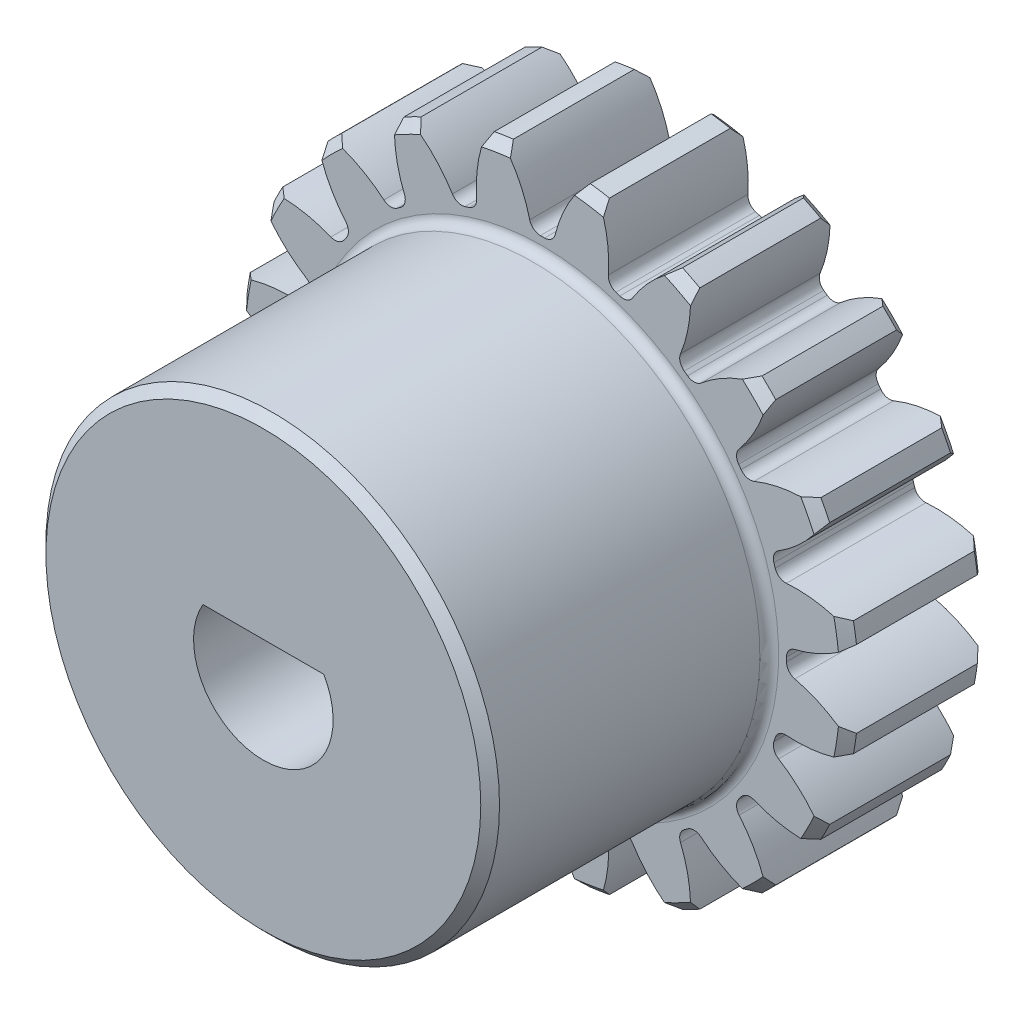
SolidWorks part; units mm, degrees
ref_plane "Front Plane" through (0, 0, 0) normal (0, 0, 1) x (1, 0, 0)
ref_plane "Top Plane" through (0, 0, 0) normal (0, 1, 0) x (1, 0, 0)
ref_plane "Right Plane" through (0, 0, 0) normal (1, 0, 0) x (0, 0, -1)
sketch "Sketch1" plane through (0, 0, 0) normal (0, 0, 1) x (1, 0, 0)
  line L0 (0, 0) -> (0, 8) construction
  line L1 (-2.5712, 8.9358) -> (2.5712, 7.0642) construction
  circle A0 centre (0, 0) radius 7 construction
  circle A1 centre (0, 0) radius 8.8 construction
  circle A2 centre (0, 0) radius 8 construction
  circle A3 centre (0, 0) radius 7.5175 construction
  circle A4 centre (0, 0) radius 6.5 construction
  circle A5 centre (0, 0) radius 2.5 construction
  point P8 (0.4, 0)
  point P13 (10, 0)
  dimension "OD" = 17.6
  dimension "Root Diameter" = 14
  dimension "Gear Pitch Diameter" = 16
  dimension "Base Diameter" = 15.0351
  dimension "Hub Diameter" = 13
  dimension "For Shaft Diameter" = 5
  dimension "Pressure Angle" = 20
  dimension "Number of Teeth" = 20
  dimension "Module" = 0.8
sketch "Sketch2" plane through (0, 0, 0) normal (1, 0, 0) x (0, 0, -1)
  line L0 (-8, 0) -> (4, 0) construction
  line L1 (4, 8.8) -> (4, -8.8) construction
  line L2 (0, -6.5) -> (-8, -6.5) construction
  line L3 (-8, 8.8) -> (4, 8.8) construction
  line L8 (-8, -6.5) -> (-8, 6.5) construction
  point P4 (0, 8.8)
  point P5 (-4, 0)
  dimension "Overall Width" = 12
  dimension "Hub Width" = 8
  dimension "Approx Set Screw Positon" = 4
  dimension "Face Width" = 4
sketch "Sketch3" plane through (0, 0, 0) normal (0, 0, 1) x (1, 0, 0)
  circle A0 centre (0, 0) radius 8.8
  circle A1 centre (0, 0) radius 8.8 construction
extrude "Boss-Extrude1" add sketch "Sketch3" against normal up to vertex (4 mm away) and the other way up to vertex (8 mm away) up to point (0, 0, -4) other way up to point (0, 0, 8)
sketch "Sketch5" plane through (0, 0, 0) normal (1, 0, 0) x (0, 0, -1)
  line L1 (0, 6.5) -> (-8, 6.5)
  line L2 (0, 6.5) -> (0, 8.8)
  line L3 (0, 8.8) -> (-8, 8.8)
  line L4 (-8, 6.5) -> (-8, 8.8)
  line L5 (-8, 0) -> (4, 0)
  line L6 (-8, 0) -> (-8, 2.5)
  line L7 (-8, 2.5) -> (4, 2.5)
  line L8 (4, 0) -> (4, 2.5)
  point P5 (0, 6.5)
  point P12 (0, 2.5)
revolve "Cut-Revolve1" cut sketch "Sketch5" angle 360 about L0
fillet "Fillet2" radius 0.2684 1 edges at (0, -6.5, 0)
chamfer "Chamfer1" distance 0.2684 angle 45 5 edges at (0, -2.5, -4) (0, -8.8, 0) (8.8, 0, -4) (0, -2.5, 8) (0, -6.5, 8)
sketch "Sketch4" plane through (0, 0, 0) normal (0, 0, 1) x (1, 0, 0)
  line L0 (6.9929, 0.3142) -> (6.9929, -0.3142)
  arc A3 (8.7308, 1.1015) -> (8.7308, -1.1015) centre (0, 0) cw
  circle A4 centre (0, 0) radius 8.8 construction
  arc A5 (6.9929, 0.3142) -> (8.7308, 1.1015) centre (6.2993, 4.157) ccw
  circle A8 centre (0, 0) radius 7 construction
  arc A9 (6.9929, -0.3142) -> (8.7308, -1.1015) centre (6.2993, -4.157) cw
  spline S0 degree 4 poles (7.5023, 0.4781) (7.5044, 0.4782) (7.5101, 0.4787) (7.521, 0.4801) (7.5386, 0.4827) (7.561, 0.4866) (7.5899, 0.4926) (7.6238, 0.5005) (7.6609, 0.5103) (7.7011, 0.5221) (7.741, 0.5348) (7.7807, 0.5484) (7.82, 0.5628) (7.8674, 0.5811) (7.9241, 0.6045) (7.9898, 0.6338) (8.0638, 0.6693) (8.1385, 0.7079) (8.2116, 0.7478) (8.2847, 0.7905) (8.355, 0.8334) (8.4273, 0.8803) (8.4937, 0.9248) (8.5672, 0.9771) (8.6263, 1.0201) (8.7033, 1.0795) (8.7486, 1.1154) (8.8011, 1.1583) (8.8243, 1.1779) (8.8386, 1.1899) knots 0 0 0 0 0 0.005377 0.015084 0.028532 0.04661 0.064855 0.092111 0.119476 0.146842 0.174209 0.201575 0.228941 0.256307 0.307035 0.361767 0.4165 0.471232 0.525964 0.580697 0.635429 0.690161 0.744894 0.799626 0.854358 0.909091 0.954545 1 1 1 1 1 construction
  spline S1 degree 4 poles (7.5023, 0.4781) (7.5044, 0.4782) (7.5101, 0.4787) (7.521, 0.4801) (7.5386, 0.4827) (7.561, 0.4866) (7.5899, 0.4926) (7.6238, 0.5005) (7.6609, 0.5103) (7.7011, 0.5221) (7.741, 0.5348) (7.7807, 0.5484) (7.82, 0.5628) (7.8674, 0.5811) (7.9241, 0.6045) (7.9898, 0.6338) (8.0638, 0.6693) (8.1385, 0.7079) (8.2116, 0.7478) (8.2847, 0.7905) (8.355, 0.8334) (8.4273, 0.8803) (8.4937, 0.9248) (8.5672, 0.9771) (8.6263, 1.0201) (8.6866, 1.0666) (8.7159, 1.0896) (8.7308, 1.1015) knots 0 0 0 0 0 0.005377 0.015084 0.028532 0.04661 0.064855 0.092111 0.119476 0.146842 0.174209 0.201575 0.228941 0.256307 0.307035 0.361767 0.4165 0.471232 0.525964 0.580697 0.635429 0.690161 0.744894 0.799626 0.854358 0.909091 0.909091 0.909091 0.909091 0.909091 construction
  spline S2 degree 4 poles (7.5023, -0.4781) (7.5044, -0.4782) (7.5101, -0.4787) (7.521, -0.4801) (7.5386, -0.4827) (7.561, -0.4866) (7.5899, -0.4926) (7.6238, -0.5005) (7.6609, -0.5103) (7.7011, -0.5221) (7.741, -0.5348) (7.7807, -0.5484) (7.82, -0.5628) (7.8674, -0.5811) (7.9241, -0.6045) (7.9898, -0.6338) (8.0638, -0.6693) (8.1385, -0.7079) (8.2116, -0.7478) (8.2847, -0.7905) (8.355, -0.8334) (8.4273, -0.8803) (8.4937, -0.9248) (8.5672, -0.9771) (8.6263, -1.0201) (8.7033, -1.0795) (8.7486, -1.1154) (8.8011, -1.1583) (8.8243, -1.1779) (8.8386, -1.1899) knots 0 0 0 0 0 0.005377 0.015084 0.028532 0.04661 0.064855 0.092111 0.119476 0.146842 0.174209 0.201575 0.228941 0.256307 0.307035 0.361767 0.4165 0.471232 0.525964 0.580697 0.635429 0.690161 0.744894 0.799626 0.854358 0.909091 0.954545 1 1 1 1 1 construction
  spline S3 degree 4 poles (7.5023, -0.4781) (7.5044, -0.4782) (7.5101, -0.4787) (7.521, -0.4801) (7.5386, -0.4827) (7.561, -0.4866) (7.5899, -0.4926) (7.6238, -0.5005) (7.6609, -0.5103) (7.7011, -0.5221) (7.741, -0.5348) (7.7807, -0.5484) (7.82, -0.5628) (7.8674, -0.5811) (7.9241, -0.6045) (7.9898, -0.6338) (8.0638, -0.6693) (8.1385, -0.7079) (8.2116, -0.7478) (8.2847, -0.7905) (8.355, -0.8334) (8.4273, -0.8803) (8.4937, -0.9248) (8.5672, -0.9771) (8.6263, -1.0201) (8.6866, -1.0666) (8.7159, -1.0896) (8.7308, -1.1015) knots 0 0 0 0 0 0.005377 0.015084 0.028532 0.04661 0.064855 0.092111 0.119476 0.146842 0.174209 0.201575 0.228941 0.256307 0.307035 0.361767 0.4165 0.471232 0.525964 0.580697 0.635429 0.690161 0.744894 0.799626 0.854358 0.909091 0.909091 0.909091 0.909091 0.909091 construction
  dimension "D1" = 0.6283
extrude "Cut-Extrude1" cut sketch "Sketch4" against normal through all both and the other way through all
fillet "Fillet1" radius 0.3142 2 edges at (6.9929, 0.3142, -2) (6.9929, -0.3142, -2)
pattern_circular "CirPattern1" count 20 over 360 about axis through (0, 0, 0) along (0, 0, 1) of "Cut-Extrude1", "Fillet1"
sketch "Sketch6" plane through (0, 0, 8) normal (0, 0, 1) x (1, 0, 0)
  line L0 (-1.7321, 1) -> (1.7321, 1)
  arc A0 (-1.7321, 1) -> (1.7321, 1) centre (0, 0) ccw
  circle A1 centre (0, 0) radius 4.0695
  dimension "D1" = 4
  dimension "D2" = 1
extrude "Boss-Extrude2" add sketch "Sketch6" against normal through all contours A1 | A0 L0
equation "\"Number of Teeth\"= 20"
equation "\"Module\"= 0.8"
equation "\"Diametral Pitch\"= 1 / \"Module\""
equation "\"Dedendum\"= 1.25 / \"Diametral Pitch\""
equation "\"Pitch Diameter\"= \"Module\" * \"Number of Teeth\""
equation "\"Root Diameter\"= \"Pitch Diameter\" - ( 2 * \"Dedendum\" )"
equation "\"Root Diameter@Sketch1\"=\"Root Diameter\""
equation "\"OD@Sketch1\" = \"Outside Diameter\""
equation "\"D1@CirPattern1\"=\"Number of Teeth\""
equation "\"Pressure Angle\"=20"
equation "\"Base Diameter\"= \"Pitch Diameter\" * cos ( \"Pressure Angle\" )"
equation "\"Outside Diameter\"= ( \"Number of Teeth\" + 2 ) / \"Diametral Pitch\""
equation "\"Pitch Angle\"= 360deg / \"Number of Teeth\""
equation "\"Alpha\"= sqr ( \"Pitch Diameter\" ^ 2 - \"Base Diameter\" ^ 2 ) / \"Base Diameter\" * 180 / PI - \"Pressure Angle\""
equation "\"Beta\"= ( \"Pitch Angle\" / 4 - \"Alpha\" )"
equation "\"Phi\"= sqr ( ( \"Outside Diameter\" / 2 ) ^ 2 - ( \"Base Diameter\" / 2 ) ^ 2 ) / ( \"Base Diameter\" / 2 )"
equation "\"Addendum\"= 1 / \"Diametral Pitch\""
equation "\"WorkingDepth\"= 2 / \"Diametral Pitch\""
equation "\"WholeDepth\"= 2.25 / \"Diametral Pitch\""
equation "\"Clearance\"= 0.25 / \"Diametral Pitch\""
equation "\"ToothThickness\"= ( pi * 2 ) / \"Diametral Pitch\""
equation "\"CircularPitch\"= pi / \"Diametral Pitch\""
equation "\"Number of Teeth@Sketch1\"=\"Number of Teeth\""
equation "\"Module@Sketch1\"=\"Module\""
equation "\"Pressure Angle@Sketch1\"=\"Pressure Angle\""
equation "\"Gear Pitch Diameter@Sketch1\"=\"Pitch Diameter\""
equation "\"Base Diameter@Sketch1\"=\"Base Diameter\""
equation "\"Fillet\"= \"Clearance\" * cos ( \"Pressure Angle\" ) * tan ( ( 90 + \"Pressure Angle\" ) / 2 )"
equation "\"D1@Fillet2\"=\"Fillet\""
equation "\"Approx Set Screw Positon@Sketch2\" = \"Hub Width@Sketch2\" / 2"
equation "\"D2\"= \"Fillet\" * 2"
equation "\"D1@Chamfer1\"=\"Fillet\""
equation "\"D1@Sketch4\"=\"CircularPitch\"*0.25"
equation "\"D1@Fillet1\"=\"CircularPitch\"*0.125"
